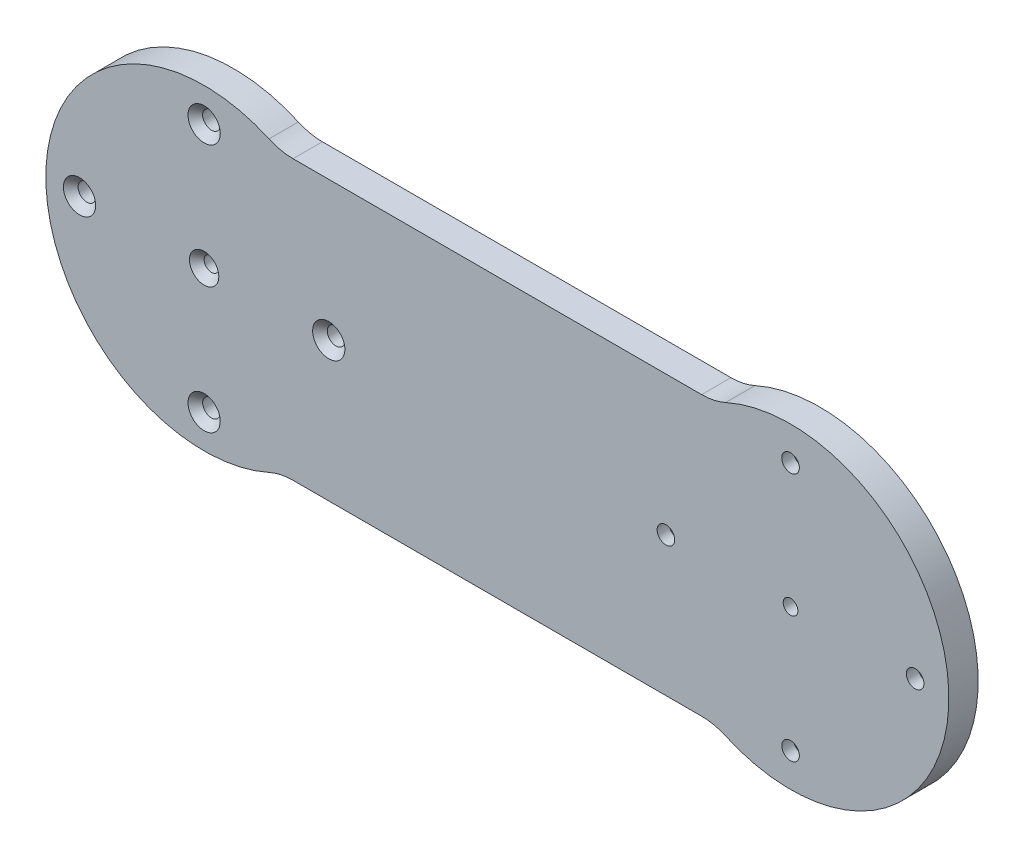
SolidWorks part; units mm, degrees
ref_plane "Спереди" through (0, 0, 0) normal (0, 0, 1) x (1, 0, 0)
ref_plane "Сверху" through (0, 0, 0) normal (0, 1, 0) x (1, 0, 0)
ref_plane "Справа" through (0, 0, 0) normal (1, 0, 0) x (0, 0, -1)
sketch "Эскиз1" plane through (0, 0, 0) normal (0, 0, 1) x (1, 0, 0)
  line L0 (-76.8877, 0) -> (191.7561, 0) construction
  line L1 (-49.6949, 47.5) -> (98.9339, 47.5)
  line L2 (-49.6949, -47.5) -> (98.9339, -47.5)
  line L3 (-49.6949, 47.5) -> (-49.6949, -47.5) construction
  line L4 (98.9339, 47.5) -> (98.9339, -47.5) construction
  arc A0 (98.9339, -47.5) -> (98.9339, 47.5) centre (124.6195, 0) ccw
  arc A1 (-49.6949, 47.5) -> (-49.6949, -47.5) centre (-75.3805, 0) ccw
  dimension "D1" = 200
  dimension "D2" = 108
  dimension "D3" = 108
  dimension "D4" = 95
  dimension "D5" = 95
extrude "Бобышка-Вытянуть1" add sketch "Эскиз1" along normal blind 10
fillet "Скругление1" radius 20 4 edges at (98.9339, -47.5, 5) (-49.6949, -47.5, 5) (98.9339, 47.5, 5) (-49.6949, 47.5, 5)
sketch "Эскиз2" plane through (0, 0, 0) normal (0, 0, -1) x (-1, 0, 0)
  line L0 (-124.6195, 42.5) -> (-124.6195, -42.5) construction
  line L1 (-124.6195, -42.5) -> (-82.1195, 0) construction
  line L2 (-82.1195, 0) -> (-167.1195, 0) construction
  circle A0 centre (-124.6195, 0) radius 42.5 construction
  circle A1 centre (-124.6195, 42.5) radius 3
  circle A2 centre (-124.6195, -42.5) radius 3
  circle A3 centre (-82.1195, 0) radius 3
  circle A4 centre (-167.1195, 0) radius 3
  circle A5 centre (-124.6195, 0) radius 2.5
  dimension "D1" = 85
  dimension "D2" = 6
  dimension "D3" = 6
  dimension "D4" = 6
  dimension "D5" = 6
  dimension "D6" = 5
extrude "Вырез-Вытянуть1" cut sketch "Эскиз2" against normal blind 10
sketch "Эскиз3" plane through (0, 0, 0) normal (0, 0, -1) x (-1, 0, 0)
  circle A0 centre (-124.6195, 42.5) radius 5.5
  circle A1 centre (-167.1195, 0) radius 5.5
  circle A2 centre (-124.6195, -42.5) radius 5.5
  circle A3 centre (-82.1195, 0) radius 5.5
  circle A4 centre (-124.6195, 0) radius 5
  dimension "D1" = 11
  dimension "D2" = 11
  dimension "D3" = 11
  dimension "D4" = 11
  dimension "D5" = 10
extrude "Вырез-Вытянуть2" cut sketch "Эскиз3" against normal blind 6
sketch "Эскиз4" plane through (0, 0, 0) normal (0, 0, -1) x (-1, 0, 0)
  circle A0 centre (75.3805, 0) radius 2.5
  dimension "D1" = 5
extrude "Вырез-Вытянуть3" cut sketch "Эскиз4" against normal blind 10
sketch "Эскиз5" plane through (0, 0, 0) normal (0, 0, -1) x (-1, 0, 0)
  circle A0 centre (75.3805, 0) radius 42.5 construction
  circle A1 centre (75.3805, 42.5) radius 3
  circle A2 centre (75.3805, -42.5) radius 3
  circle A3 centre (32.8805, 0) radius 3
  circle A4 centre (117.8805, 0) radius 3
  dimension "D1" = 85
  dimension "D2" = 6
  dimension "D3" = 6
  dimension "D4" = 6
  dimension "D5" = 6
extrude "Вырез-Вытянуть4" cut sketch "Эскиз5" against normal blind 10
chamfer "Фаска1" distance 2.5 angle 45 5 edges at (-35.8805, 0, 10) (-77.8805, 0, 10) (-78.3805, 42.5, 10) (-120.8805, 0, 10) (-78.3805, -42.5, 10)
